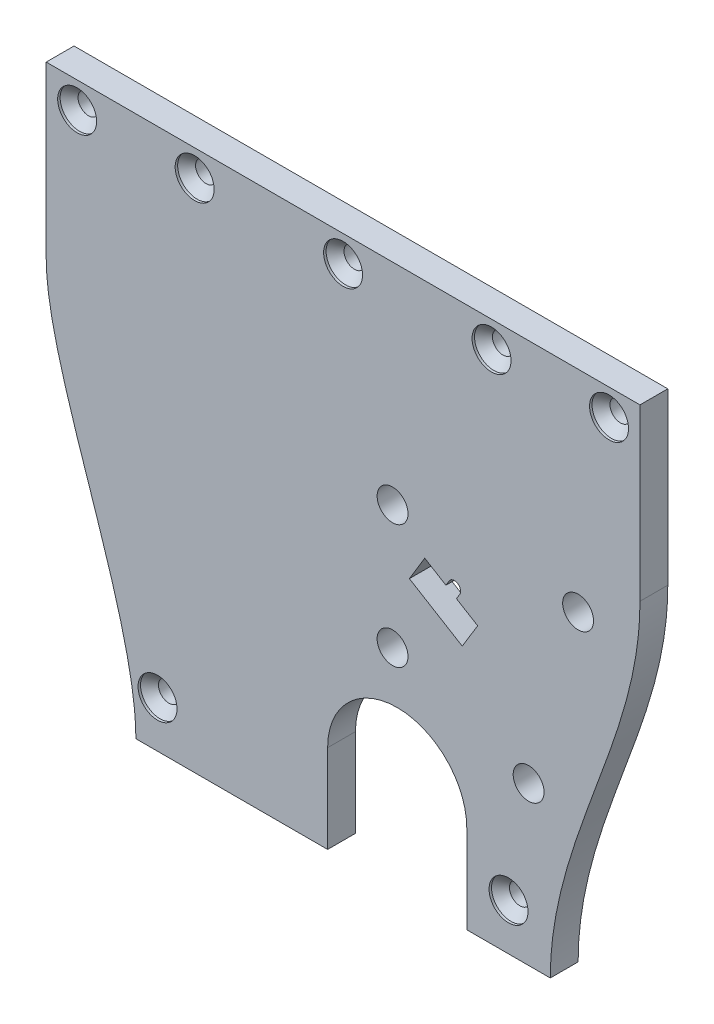
SolidWorks part; units mm, degrees
ref_plane "Front Plane" through (0, 0, 0) normal (0, 0, 1) x (1, 0, 0)
ref_plane "Top Plane" through (0, 0, 0) normal (0, 1, 0) x (1, 0, 0)
ref_plane "Right Plane" through (0, 0, 0) normal (1, 0, 0) x (0, 0, -1)
sketch "Sketch1" plane through (0, 0, 0) normal (0, 0, 1) x (1, 0, 0)
  line L0 (-96, 87.5) -> (0, 87.5)
  line L1 (-96, 87.5) -> (-96, 60) construction
  line L2 (0, 60) -> (0, 87.5) construction
  line L3 (-96, 87.5) -> (-96, 60)
  line L4 (0, 60) -> (0, 87.5)
  line L5 (-81.5, 0) -> (-50.5, 0)
  line L8 (-50.5, 14.25) -> (-50.5, 0)
  line L9 (-28, 14.25) -> (-28, 0)
  line L10 (-28, 0) -> (-14.5, 0) construction
  line L11 (-28, 0) -> (-14.5, 0)
  arc A0 (-28, 14.25) -> (-50.5, 14.25) centre (-39.25, 14.25) ccw
  circle A1 centre (-91, 83.25) radius 1.5
  circle A2 centre (-72, 83.25) radius 1.5
  circle A3 centre (-48, 83.25) radius 1.5
  circle A4 centre (-5, 83.25) radius 1.5
  circle A5 centre (-24, 83.25) radius 1.5
  circle A6 centre (-21.25, 7.5) radius 1.5
  circle A7 centre (-78, 7.5) radius 1.5
  spline S0 degree 3 poles (758.7403, -459.0464) (-1035.6768, 781.853) (866.7995, -708.7239) (-959.7206, 478.239) knots -2.661345 -2.661345 -2.661345 -2.661345 3.688798 3.688798 3.688798 3.688798 only from (-96, 60) to (-81.5, 0) construction
  spline S1 degree 3 poles (-926.4822, 436.3245) (70.4103, 143.3489) (-40.5796, 39.2803) (-23.296, -115.324) (977.5002, -126.213) knots -2.74375 -2.74375 -2.74375 -2.74375 0.602811 3.81543 3.81543 3.81543 3.81543 only from (0, 60) to (-14.5, 0) construction
  spline S2 degree 3 poles (-96, 60) (-96, 44.4793) (-81.5, 17.4381) (-81.5, 0) knots 0 0 0 0 1 1 1 1
  spline S3 degree 3 poles (0, 60) (0, 47.4409) (-8.7408, 28.352) (-14.5, 8.0884) (-14.5, 0) knots 0 0 0 0 0.602811 1 1 1 1
  dimension "D1" = 22.5
  dimension "D2" = 3
extrude "Boss-Extrude1" add sketch "Sketch1" along normal blind 4.5
sketch "Sketch2" plane through (0, 0, 4.5) normal (0, 0, 1) x (1, 0, 0)
  line L0 (0, 87.5) -> (-96, 87.5) construction
  line L1 (0, 60) -> (0, 87.5) construction
  line L2 (-10, 53.5) -> (-40, 53.5) construction
  line L3 (-40, 53.5) -> (-40, 33.5) construction
  line L4 (-40, 33.5) -> (-37.5, 33.5) construction
  line L7 (-10.1117, 51.0025) -> (-10, 53.5) construction
  circle A0 centre (-10, 53.5) radius 2.5
  circle A1 centre (-40, 53.5) radius 2.5
  circle A2 centre (-40, 33.5) radius 2.5
  circle A3 centre (-18, 25.5) radius 2.5
  dimension "D1" = 5
  dimension "D2" = 34
  dimension "D3" = 10
  dimension "D4" = 30
  dimension "D5" = 20
  dimension "D6" = 8
  dimension "D7" = 22
extrude "Cut-Extrude1" cut sketch "Sketch2" against normal through all
sketch "Sketch3" plane through (0, 0, 4.5) normal (0, 0, 1) x (1, 0, 0)
  circle A0 centre (-30.0011, 46.8996) radius 1
extrude "Cut-Extrude2" cut sketch "Sketch3" against normal through all
sketch "Sketch4" plane through (0, 0, 0) normal (0, 0, -1) x (-1, 0, 0)
  line L0 (28.7284, 39.3484) -> (37.2823, 44.5281)
  line L1 (28.7284, 39.3484) -> (26.2421, 43.4543)
  line L2 (37.2823, 44.5281) -> (34.7961, 48.634)
  line L3 (26.2421, 43.4543) -> (29.6644, 45.5266)
  line L4 (30.0011, 46.8996) -> (46.9486, 18.9117) construction
  line L5 (29.1259, 46.4159) -> (29.6644, 45.5266)
  line L6 (30.8565, 47.4175) -> (31.3745, 46.5621)
  line L7 (31.3745, 46.5621) -> (34.7961, 48.634)
  circle A0 centre (39.25, 14.25) radius 9 construction
  circle A1 centre (30.0011, 46.8996) radius 1 construction
  arc A2 (30.8565, 47.4175) -> (29.1259, 46.4159) centre (30.0011, 46.8996) ccw
  point P14 (33.0053, 41.9382)
  dimension "D1" = 18
  dimension "D2" = 10
  dimension "D3" = 4.8
extrude "Cut-Extrude3" cut sketch "Sketch4" against normal through all
hole_wizard "CSK for M3 Countersunk Flat Head Screw1" positions "Sketch5" profile "Sketch6" countersink size "M3" standard "ISO" end condition through all
sketch "Sketch5" plane through (0, 0, 4.5) normal (0, 0, 1) x (1, 0, 0)
  point P0 (-91, 83.25)
  point P3 (-72, 83.25)
  point P6 (-48, 83.25)
  point P9 (-24, 83.25)
  point P12 (-5, 83.25)
  point P15 (-21.25, 7.5)
  point P18 (-78, 7.5)
sketch "Sketch6" plane through (-91, 83.25, 4.5) normal (1, 0, 0) x (0, -1, 0)
  line L0 (0, 0) -> (0, 4.5)
  line L1 (0, 4.5) -> (1.7, 4.5)
  line L2 (1.7, 4.5) -> (1.7, 1.85)
  line L3 (1.7, 1.85) -> (3.15, 0.4)
  line L4 (3.15, 0.4) -> (3.15, 0)
  line L6 (3.15, 0) -> (0, 0)
  line L7 (-1.7, 1.85) -> (-3.15, 0.4) construction
  line L11 (0, -6.35) -> (0, 107.95) construction
  dimension "Thru Hole Dia." = 3.4
  dimension "Thru Hole Depth" = 4.5
  dimension "C'Sink Dia." = 6.3
  dimension "C'Sink Angle" = 90
  dimension "Head Clearance" = 0.4
